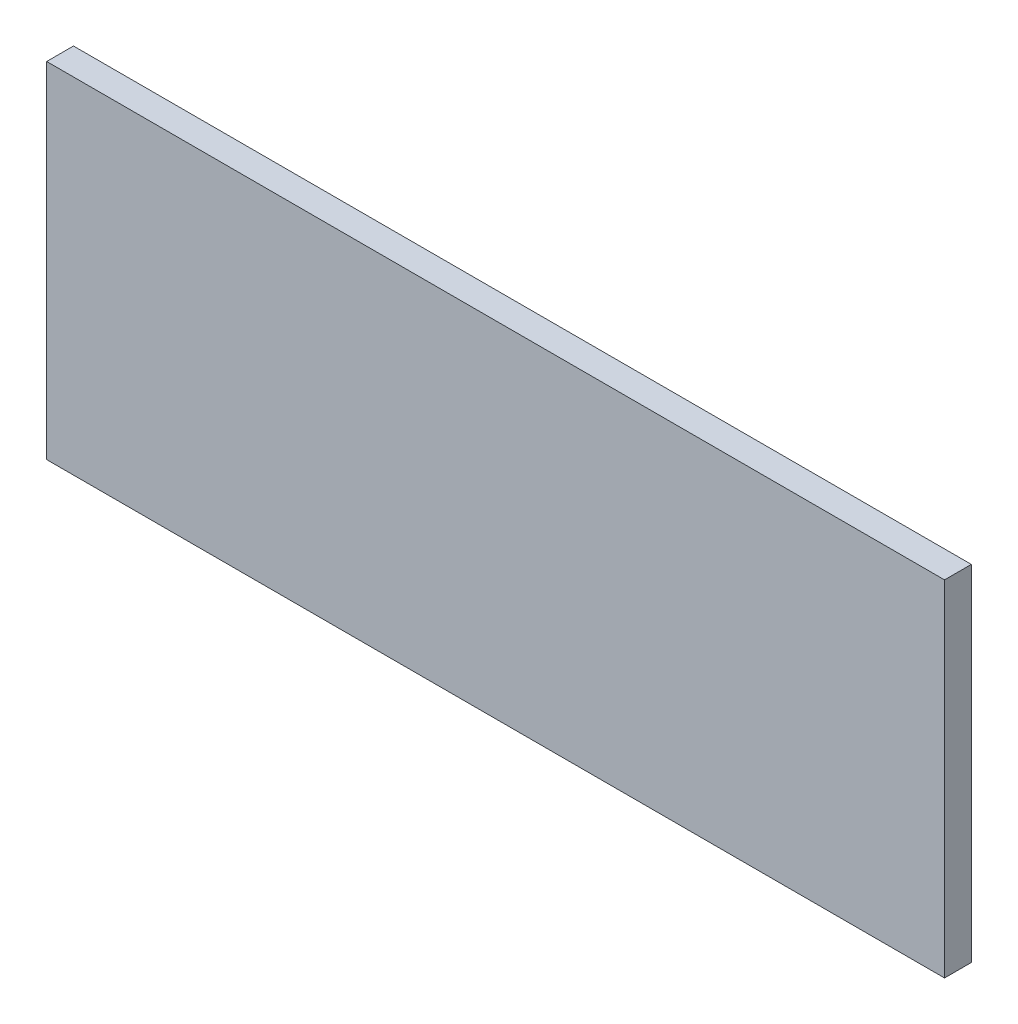
SolidWorks part; units mm, degrees
ref_plane "Front Plane" through (0, 0, 0) normal (0, 0, 1) x (1, 0, 0)
ref_plane "Top Plane" through (0, 0, 0) normal (0, 1, 0) x (1, 0, 0)
ref_plane "Right Plane" through (0, 0, 0) normal (1, 0, 0) x (0, 0, -1)
sketch "Sketch1" plane through (0, 0, 0) normal (0, 0, 1) x (1, 0, 0)
  line L1 (319.05, 19.05) -> (-319.05, 19.05)
  line L2 (319.05, 19.05) -> (319.05, -226)
  line L3 (319.05, -226) -> (-319.05, -226)
  line L4 (-319.05, 19.05) -> (-319.05, -226)
  dimension "D1" = 245.05
  dimension "D2" = 638.1
extrude "Boss-Extrude1" add sketch "Sketch1" along normal blind 19.05
